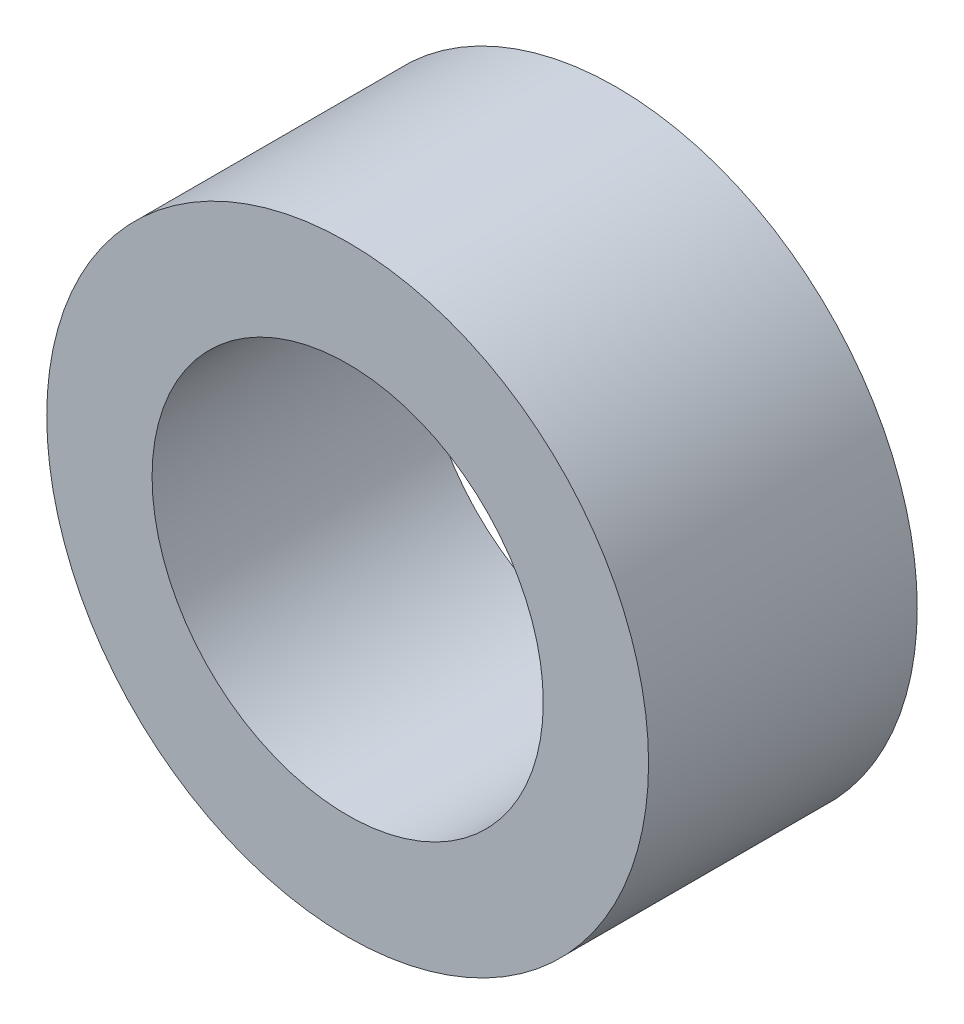
SolidWorks part; units mm, degrees
ref_plane "Front" through (0, 0, 0) normal (0, 0, 1) x (1, 0, 0)
ref_plane "Top" through (0, 0, 0) normal (0, 1, 0) x (1, 0, 0)
ref_plane "Right" through (0, 0, 0) normal (1, 0, 0) x (0, 0, -1)
sketch "Sketch1" plane through (0, 0, 0) normal (0, 0, 1) x (1, 0, 0)
  circle A0 centre (0, 0) radius 6.9342
  circle A2 centre (0, 0) radius 10.668
  dimension "D1" = 13.8684
  dimension "D2" = 21.336
extrude "Boss-Extrude1" add sketch "Sketch1" along normal blind 9.525
